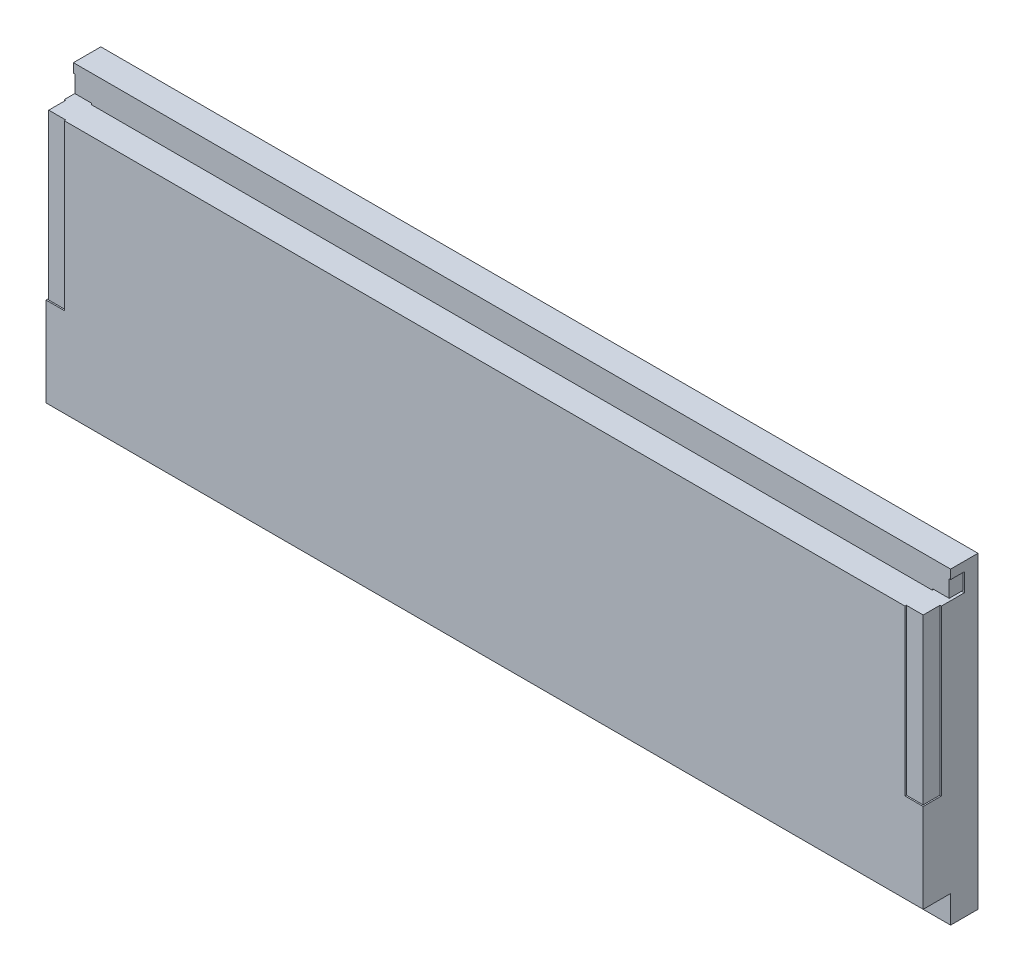
SolidWorks part; units mm, degrees
ref_plane "Front Plane" through (0, 0, 0) normal (0, 0, 1) x (1, 0, 0)
ref_plane "Top Plane" through (0, 0, 0) normal (0, 1, 0) x (1, 0, 0)
ref_plane "Right Plane" through (0, 0, 0) normal (1, 0, 0) x (0, 0, -1)
sketch "Sketch1" plane through (0, 0, 0) normal (0, 0, 1) x (1, 0, 0)
  line L1 (960, 337.5) -> (-960, 337.5)
  line L2 (960, 337.5) -> (960, -337.5)
  line L3 (960, -337.5) -> (-960, -337.5)
  line L4 (-960, 337.5) -> (-960, -337.5)
  line L5 (960, 337.5) -> (-960, -337.5) construction
  line L6 (960, -337.5) -> (-960, 337.5) construction
  point P0 (0, 0)
  dimension "D1" = 1920
  dimension "D2" = 675
extrude "Boss-Extrude1" add sketch "Sketch1" along normal blind 120
ref_plane "Plane1" through (960, 0, 0) normal (1, 0, 0) x (0, 0, -1)
sketch "Sketch2" plane through (960, 0, 0) normal (1, 0, 0) x (0, 0, -1)
  line L7 (-60, 277.5) -> (-120, 277.5)
  line L8 (-60, 277.5) -> (-60, 337.5)
  line L9 (0, -277.5) -> (-60, -277.5)
  line L10 (-60, -277.5) -> (-60, 277.5)
  line L11 (-60, 277.5) -> (0, 277.5)
  line L12 (0, -277.5) -> (-60, -277.5) construction
  line L13 (-60, -277.5) -> (-60, 277.5) construction
  line L14 (-60, 277.5) -> (0, 277.5) construction
  line L15 (-60, 337.5) -> (-120, 337.5)
  line L16 (-120, 277.5) -> (-120, 337.5)
  line L17 (-60, -277.5) -> (-120, -277.5)
  line L18 (-60, -277.5) -> (-60, -337.5)
  line L19 (-60, -337.5) -> (-120, -337.5)
  line L20 (-120, -277.5) -> (-120, -337.5)
  dimension "D1" = 60
extrude "Cut-Extrude1" cut sketch "Sketch2" against normal through all
ref_plane "Plane2" through (0, 277.5, 0) normal (0, 1, 0) x (1, 0, 0)
sketch "Sketch3" plane through (0, 277.5, 0) normal (0, 1, 0) x (1, 0, 0)
  line L6 (-960, -80) -> (960, -80)
  line L7 (-960, -80) -> (-957, -80)
  line L8 (957, -117) -> (957, -63)
  line L9 (957, -63) -> (-957, -63)
  line L10 (-957, -63) -> (-957, -117)
  line L11 (-957, -117) -> (957, -117)
  line L12 (957, -117) -> (957, -63)
  line L13 (-960, -80) -> (-960, -120)
  line L14 (-957, -80) -> (-957, -117)
  line L15 (-957, -117) -> (-920, -117)
  line L16 (-960, -120) -> (-920, -120)
  line L18 (-920, -120) -> (-920, -117)
  line L19 (957, -80) -> (960, -80)
  dimension "D1" = 3
  dimension "D2" = 40
extrude "Cut-Extrude2" cut sketch "Sketch3" against normal blind 360 contours L16 L18 L15 L14 L7 L13
ref_plane "Plane3" through (0, 0, 60) normal (0, 0, 1) x (1, 0, 0)
sketch "Sketch4" plane through (0, 0, 60) normal (0, 0, 1) x (1, 0, 0)
  line L2 (-957, 280.5) -> (-920, 280.5)
  line L5 (-957, 277.5) -> (-957, 337.5)
  line L6 (-957, 280.5) -> (-957, 317.5)
  line L7 (-960, 317.5) -> (-957, 317.5)
  line L8 (-920, 277.5) -> (-920, 337.5)
  line L9 (-920, 277.5) -> (-920, 280.5)
  line L10 (-920, 277.5) -> (-960, 277.5)
  line L12 (-920, 317.5) -> (-920, 337.5) construction
  line L15 (-960, 317.5) -> (-960, 277.5)
  dimension "D2" = 3
  dimension "D3" = 40
extrude "Cut-Extrude3" cut sketch "Sketch4" against normal blind 30
mirror "Mirror1" about plane through (0, 0, 0) normal (1, 0, 0) of "Cut-Extrude3", "Cut-Extrude2"
